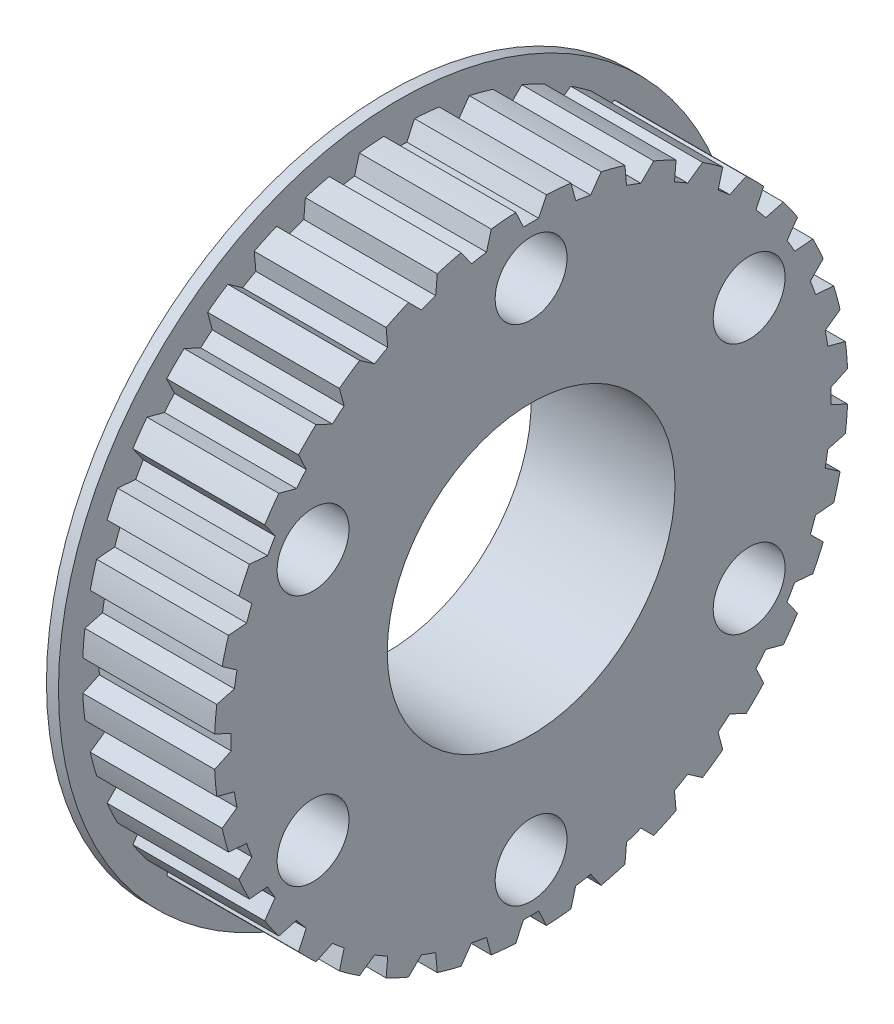
SolidWorks part; units mm, degrees
ref_plane "Front Plane" through (0, 0, 0) normal (0, 0, 1) x (1, 0, 0)
ref_plane "Top Plane" through (0, 0, 0) normal (0, 1, 0) x (1, 0, 0)
ref_plane "Right Plane" through (0, 0, 0) normal (1, 0, 0) x (0, 0, -1)
sketch "Sketch1" plane through (0, 0, 0) normal (1, 0, 0) x (0, 0, -1)
  line L0 (0, 26.425) -> (0, 0) construction
  circle A0 centre (0, 0) radius 26.425
  circle A1 centre (0, 0) radius 12
  dimension "D1" = 52.85
  dimension "D2" = 24
extrude "Boss-Extrude1" add sketch "Sketch1" along normal blind 11
sketch "Sketch2" plane through (0, 0, 0) normal (-1, 0, 0) x (0, 0, 1)
  line L0 (0, 0) -> (0, 26.425) construction
  line L1 (1.2771, 26.3941) -> (0.6349, 25.0169)
  line L2 (-1.2771, 26.3941) -> (-0.6349, 25.0169)
  line L3 (5.841, 25.7714) -> (4.9694, 24.5266)
  line L4 (3.3256, 26.2149) -> (3.7189, 24.7471)
  line L5 (10.2274, 24.3656) -> (9.1529, 23.2911)
  line L6 (7.8272, 25.2392) -> (7.9597, 23.7254)
  line L7 (14.3031, 22.2194) -> (13.0583, 21.3478)
  line L8 (12.091, 23.4965) -> (11.9586, 21.9828)
  line L9 (17.9441, 19.3982) -> (16.567, 18.756)
  line L10 (15.9875, 21.04) -> (15.5942, 19.5722)
  line L11 (21.04, 15.9875) -> (19.5722, 15.5942)
  line L12 (19.3982, 17.9441) -> (18.756, 16.567)
  line L13 (23.4965, 12.091) -> (21.9828, 11.9586)
  line L14 (22.2194, 14.3031) -> (21.3478, 13.0583)
  line L15 (25.2392, 7.8272) -> (23.7254, 7.9597)
  line L16 (24.3656, 10.2274) -> (23.2911, 9.1529)
  line L17 (26.2149, 3.3256) -> (24.7471, 3.7189)
  line L18 (25.7714, 5.841) -> (24.5266, 4.9694)
  line L19 (26.3941, -1.2771) -> (25.0169, -0.6349)
  line L20 (26.3941, 1.2771) -> (25.0169, 0.6349)
  line L21 (25.7714, -5.841) -> (24.5266, -4.9694)
  line L22 (26.2149, -3.3256) -> (24.7471, -3.7189)
  line L23 (24.3656, -10.2274) -> (23.2911, -9.1529)
  line L24 (25.2392, -7.8272) -> (23.7254, -7.9597)
  line L25 (22.2194, -14.3031) -> (21.3478, -13.0583)
  line L26 (23.4965, -12.091) -> (21.9828, -11.9586)
  line L27 (19.3982, -17.9441) -> (18.756, -16.567)
  line L28 (21.04, -15.9875) -> (19.5722, -15.5942)
  line L29 (15.9875, -21.04) -> (15.5942, -19.5722)
  line L30 (17.9441, -19.3982) -> (16.567, -18.756)
  line L31 (12.091, -23.4965) -> (11.9586, -21.9828)
  line L32 (14.3031, -22.2194) -> (13.0583, -21.3478)
  line L33 (7.8272, -25.2392) -> (7.9597, -23.7254)
  line L34 (10.2274, -24.3656) -> (9.1529, -23.2911)
  line L35 (3.3256, -26.2149) -> (3.7189, -24.7471)
  line L36 (5.841, -25.7714) -> (4.9694, -24.5266)
  line L37 (-1.2771, -26.3941) -> (-0.6349, -25.0169)
  line L38 (1.2771, -26.3941) -> (0.6349, -25.0169)
  line L39 (-5.841, -25.7714) -> (-4.9694, -24.5266)
  line L40 (-3.3256, -26.2149) -> (-3.7189, -24.7471)
  line L41 (-10.2274, -24.3656) -> (-9.1529, -23.2911)
  line L42 (-7.8272, -25.2392) -> (-7.9597, -23.7254)
  line L43 (-14.3031, -22.2194) -> (-13.0583, -21.3478)
  line L44 (-12.091, -23.4965) -> (-11.9586, -21.9828)
  line L45 (-17.9441, -19.3982) -> (-16.567, -18.756)
  line L46 (-15.9875, -21.04) -> (-15.5942, -19.5722)
  line L47 (-21.04, -15.9875) -> (-19.5722, -15.5942)
  line L48 (-19.3982, -17.9441) -> (-18.756, -16.567)
  line L49 (-23.4965, -12.091) -> (-21.9828, -11.9586)
  line L50 (-22.2194, -14.3031) -> (-21.3478, -13.0583)
  line L51 (-25.2392, -7.8272) -> (-23.7254, -7.9597)
  line L52 (-24.3656, -10.2274) -> (-23.2911, -9.1529)
  line L53 (-26.2149, -3.3256) -> (-24.7471, -3.7189)
  line L54 (-25.7714, -5.841) -> (-24.5266, -4.9694)
  line L55 (-26.3941, 1.2771) -> (-25.0169, 0.6349)
  line L56 (-26.3941, -1.2771) -> (-25.0169, -0.6349)
  line L57 (-25.7714, 5.841) -> (-24.5266, 4.9694)
  line L58 (-26.2149, 3.3256) -> (-24.7471, 3.7189)
  line L59 (-24.3656, 10.2274) -> (-23.2911, 9.1529)
  line L60 (-25.2392, 7.8272) -> (-23.7254, 7.9597)
  line L61 (-22.2194, 14.3031) -> (-21.3478, 13.0583)
  line L62 (-23.4965, 12.091) -> (-21.9828, 11.9586)
  line L63 (-19.3982, 17.9441) -> (-18.756, 16.567)
  line L64 (-21.04, 15.9875) -> (-19.5722, 15.5942)
  line L65 (-15.9875, 21.04) -> (-15.5942, 19.5722)
  line L66 (-17.9441, 19.3982) -> (-16.567, 18.756)
  line L67 (-12.091, 23.4965) -> (-11.9586, 21.9828)
  line L68 (-14.3031, 22.2194) -> (-13.0583, 21.3478)
  line L69 (-7.8272, 25.2392) -> (-7.9597, 23.7254)
  line L70 (-10.2274, 24.3656) -> (-9.1529, 23.2911)
  line L71 (-3.3256, 26.2149) -> (-3.7189, 24.7471)
  line L72 (-5.841, 25.7714) -> (-4.9694, 24.5266)
  circle A0 centre (0, 0) radius 26.425 construction
  arc A1 (1.2771, 26.3941) -> (-1.2771, 26.3941) centre (0, 0) ccw
  arc A2 (0.6349, 25.0169) -> (-0.6349, 25.0169) centre (0, 0) ccw
  arc A3 (5.841, 25.7714) -> (3.3256, 26.2149) centre (0, 0) ccw
  arc A4 (4.9694, 24.5266) -> (3.7189, 24.7471) centre (0, 0) ccw
  arc A5 (10.2274, 24.3656) -> (7.8272, 25.2392) centre (0, 0) ccw
  arc A6 (9.1529, 23.2911) -> (7.9597, 23.7254) centre (0, 0) ccw
  arc A7 (14.3031, 22.2194) -> (12.091, 23.4965) centre (0, 0) ccw
  arc A8 (13.0583, 21.3478) -> (11.9586, 21.9828) centre (0, 0) ccw
  arc A9 (17.9441, 19.3982) -> (15.9875, 21.04) centre (0, 0) ccw
  arc A10 (16.567, 18.756) -> (15.5942, 19.5722) centre (0, 0) ccw
  arc A11 (21.04, 15.9875) -> (19.3982, 17.9441) centre (0, 0) ccw
  arc A12 (19.5722, 15.5942) -> (18.756, 16.567) centre (0, 0) ccw
  arc A13 (23.4965, 12.091) -> (22.2194, 14.3031) centre (0, 0) ccw
  arc A14 (21.9828, 11.9586) -> (21.3478, 13.0583) centre (0, 0) ccw
  arc A15 (25.2392, 7.8272) -> (24.3656, 10.2274) centre (0, 0) ccw
  arc A16 (23.7254, 7.9597) -> (23.2911, 9.1529) centre (0, 0) ccw
  arc A17 (26.2149, 3.3256) -> (25.7714, 5.841) centre (0, 0) ccw
  arc A18 (24.7471, 3.7189) -> (24.5266, 4.9694) centre (0, 0) ccw
  arc A19 (26.3941, -1.2771) -> (26.3941, 1.2771) centre (0, 0) ccw
  arc A20 (25.0169, -0.6349) -> (25.0169, 0.6349) centre (0, 0) ccw
  arc A21 (25.7714, -5.841) -> (26.2149, -3.3256) centre (0, 0) ccw
  arc A22 (24.5266, -4.9694) -> (24.7471, -3.7189) centre (0, 0) ccw
  arc A23 (24.3656, -10.2274) -> (25.2392, -7.8272) centre (0, 0) ccw
  arc A24 (23.2911, -9.1529) -> (23.7254, -7.9597) centre (0, 0) ccw
  arc A25 (22.2194, -14.3031) -> (23.4965, -12.091) centre (0, 0) ccw
  arc A26 (21.3478, -13.0583) -> (21.9828, -11.9586) centre (0, 0) ccw
  arc A27 (19.3982, -17.9441) -> (21.04, -15.9875) centre (0, 0) ccw
  arc A28 (18.756, -16.567) -> (19.5722, -15.5942) centre (0, 0) ccw
  arc A29 (15.9875, -21.04) -> (17.9441, -19.3982) centre (0, 0) ccw
  arc A30 (15.5942, -19.5722) -> (16.567, -18.756) centre (0, 0) ccw
  arc A31 (12.091, -23.4965) -> (14.3031, -22.2194) centre (0, 0) ccw
  arc A32 (11.9586, -21.9828) -> (13.0583, -21.3478) centre (0, 0) ccw
  arc A33 (7.8272, -25.2392) -> (10.2274, -24.3656) centre (0, 0) ccw
  arc A34 (7.9597, -23.7254) -> (9.1529, -23.2911) centre (0, 0) ccw
  arc A35 (3.3256, -26.2149) -> (5.841, -25.7714) centre (0, 0) ccw
  arc A36 (3.7189, -24.7471) -> (4.9694, -24.5266) centre (0, 0) ccw
  arc A37 (-1.2771, -26.3941) -> (1.2771, -26.3941) centre (0, 0) ccw
  arc A38 (-0.6349, -25.0169) -> (0.6349, -25.0169) centre (0, 0) ccw
  arc A39 (-5.841, -25.7714) -> (-3.3256, -26.2149) centre (0, 0) ccw
  arc A40 (-4.9694, -24.5266) -> (-3.7189, -24.7471) centre (0, 0) ccw
  arc A41 (-10.2274, -24.3656) -> (-7.8272, -25.2392) centre (0, 0) ccw
  arc A42 (-9.1529, -23.2911) -> (-7.9597, -23.7254) centre (0, 0) ccw
  arc A43 (-14.3031, -22.2194) -> (-12.091, -23.4965) centre (0, 0) ccw
  arc A44 (-13.0583, -21.3478) -> (-11.9586, -21.9828) centre (0, 0) ccw
  arc A45 (-17.9441, -19.3982) -> (-15.9875, -21.04) centre (0, 0) ccw
  arc A46 (-16.567, -18.756) -> (-15.5942, -19.5722) centre (0, 0) ccw
  arc A47 (-21.04, -15.9875) -> (-19.3982, -17.9441) centre (0, 0) ccw
  arc A48 (-19.5722, -15.5942) -> (-18.756, -16.567) centre (0, 0) ccw
  arc A49 (-23.4965, -12.091) -> (-22.2194, -14.3031) centre (0, 0) ccw
  arc A50 (-21.9828, -11.9586) -> (-21.3478, -13.0583) centre (0, 0) ccw
  arc A51 (-25.2392, -7.8272) -> (-24.3656, -10.2274) centre (0, 0) ccw
  arc A52 (-23.7254, -7.9597) -> (-23.2911, -9.1529) centre (0, 0) ccw
  arc A53 (-26.2149, -3.3256) -> (-25.7714, -5.841) centre (0, 0) ccw
  arc A54 (-24.7471, -3.7189) -> (-24.5266, -4.9694) centre (0, 0) ccw
  arc A55 (-26.3941, 1.2771) -> (-26.3941, -1.2771) centre (0, 0) ccw
  arc A56 (-25.0169, 0.6349) -> (-25.0169, -0.6349) centre (0, 0) ccw
  arc A57 (-25.7714, 5.841) -> (-26.2149, 3.3256) centre (0, 0) ccw
  arc A58 (-24.5266, 4.9694) -> (-24.7471, 3.7189) centre (0, 0) ccw
  arc A59 (-24.3656, 10.2274) -> (-25.2392, 7.8272) centre (0, 0) ccw
  arc A60 (-23.2911, 9.1529) -> (-23.7254, 7.9597) centre (0, 0) ccw
  arc A61 (-22.2194, 14.3031) -> (-23.4965, 12.091) centre (0, 0) ccw
  arc A62 (-21.3478, 13.0583) -> (-21.9828, 11.9586) centre (0, 0) ccw
  arc A63 (-19.3982, 17.9441) -> (-21.04, 15.9875) centre (0, 0) ccw
  arc A64 (-18.756, 16.567) -> (-19.5722, 15.5942) centre (0, 0) ccw
  arc A65 (-15.9875, 21.04) -> (-17.9441, 19.3982) centre (0, 0) ccw
  arc A66 (-15.5942, 19.5722) -> (-16.567, 18.756) centre (0, 0) ccw
  arc A67 (-12.091, 23.4965) -> (-14.3031, 22.2194) centre (0, 0) ccw
  arc A68 (-11.9586, 21.9828) -> (-13.0583, 21.3478) centre (0, 0) ccw
  arc A69 (-7.8272, 25.2392) -> (-10.2274, 24.3656) centre (0, 0) ccw
  arc A70 (-7.9597, 23.7254) -> (-9.1529, 23.2911) centre (0, 0) ccw
  arc A71 (-3.3256, 26.2149) -> (-5.841, 25.7714) centre (0, 0) ccw
  arc A72 (-3.7189, 24.7471) -> (-4.9694, 24.5266) centre (0, 0) ccw
  point P10 (0, 25.025)
  point P18 (4.3455, 24.6448)
  point P23 (8.5591, 23.5158)
  point P28 (12.5125, 21.6723)
  point P33 (16.0858, 19.1703)
  point P38 (19.1703, 16.0858)
  point P43 (21.6723, 12.5125)
  point P48 (23.5158, 8.5591)
  point P53 (24.6448, 4.3455)
  point P58 (25.025, 0)
  point P63 (24.6448, -4.3455)
  point P68 (23.5158, -8.5591)
  point P73 (21.6723, -12.5125)
  point P78 (19.1703, -16.0858)
  point P83 (16.0858, -19.1703)
  point P88 (12.5125, -21.6723)
  point P93 (8.5591, -23.5158)
  point P98 (4.3455, -24.6448)
  point P103 (0, -25.025)
  point P108 (-4.3455, -24.6448)
  point P113 (-8.5591, -23.5158)
  point P118 (-12.5125, -21.6723)
  point P123 (-16.0858, -19.1703)
  point P128 (-19.1703, -16.0858)
  point P133 (-21.6723, -12.5125)
  point P138 (-23.5158, -8.5591)
  point P143 (-24.6448, -4.3455)
  point P148 (-25.025, 0)
  point P153 (-24.6448, 4.3455)
  point P158 (-23.5158, 8.5591)
  point P159 (0, 0)
  point P161 (-21.6723, 12.5125)
  point P166 (-19.1703, 16.0858)
  point P171 (-16.0858, 19.1703)
  point P176 (-12.5125, 21.6723)
  point P181 (-8.5591, 23.5158)
  point P186 (-4.3455, 24.6448)
  dimension "D1" = 1.4
  dimension "D2" = 25
  dimension "D3" = 0.635
  dimension "D4" = 36
extrude "Cut-Extrude1" cut sketch "Sketch2" against normal through all
sketch "Sketch3" plane through (0, 0, 0) normal (-1, 0, 0) x (0, 0, 1)
  circle A0 centre (0, 0) radius 12
  circle A1 centre (0, 0) radius 28.425
  arc A2 (-1.2771, 26.3941) -> (-3.3256, 26.2149) centre (0, 0) ccw construction
  dimension "D1" = 2
extrude "Boss-Extrude2" add sketch "Sketch3" along normal blind 1
sketch "Sketch4" plane through (-1, 0, 0) normal (-1, 0, 0) x (0, 0, 1)
  line L0 (0, 0) -> (0, 21) construction
  circle A0 centre (0, 21) radius 3
  circle A1 centre (18.1865, 10.5) radius 3
  circle A2 centre (18.1865, -10.5) radius 3
  circle A3 centre (0, -21) radius 3
  circle A4 centre (-18.1865, -10.5) radius 3
  circle A5 centre (-18.1865, 10.5) radius 3
  point P16 (0, 0)
  dimension "D1" = 6
  dimension "D2" = 21
  dimension "D3" = 6
extrude "Cut-Extrude2" cut sketch "Sketch4" against normal through all
